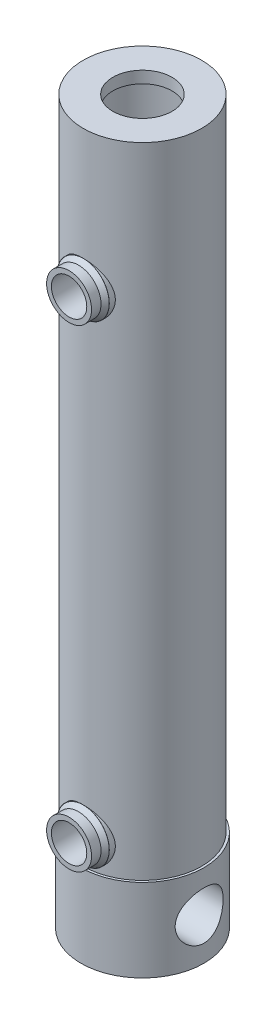
SolidWorks part; units mm, degrees
ref_plane "Plan de face" through (0, 0, 0) normal (0, 0, 1) x (1, 0, 0)
ref_plane "Plan de dessus" through (0, 0, 0) normal (0, 1, 0) x (1, 0, 0)
ref_plane "Plan de droite" through (0, 0, 0) normal (1, 0, 0) x (0, 0, -1)
sketch "Esquisse1" plane through (0, 0, 0) normal (0, 0, 1) x (1, 0, 0)
  line L0 (0, 0) -> (25, 0)
  line L1 (25, 0) -> (25, 270)
  line L2 (25, 270) -> (12.5, 270)
  line L3 (12.5, 270) -> (12.5, 265)
  line L4 (12.5, 265) -> (20, 265)
  line L5 (20, 265) -> (20, 3)
  line L6 (20, 3) -> (0, 3)
  line L7 (0, 3) -> (0, 0)
  line L8 (0, 3) -> (0, 270) construction
  line L9 (0, 270) -> (12.5, 270) construction
  dimension "D1" = 25
  dimension "D2" = 20
  dimension "D3" = 3
  dimension "D4" = 5
  dimension "D5" = 12.5
  dimension "D6" = 270
revolve "Révolution1" add sketch "Esquisse1" angle 360 about L8
sketch "Esquisse2" plane through (0, 0, 0) normal (0, -1, 0) x (-1, 0, 0)
  circle A0 centre (0, 0) radius 26
  dimension "D1" = 52
extrude "Boss.-Extru.1" add sketch "Esquisse2" along normal blind 35
sketch "Esquisse3" plane through (0, 0, 0) normal (0, 0, 1) x (1, 0, 0)
  line L0 (0, -17.5) -> (0, 0) construction
  line L1 (0, 0) -> (0, 211.5) construction
  circle A0 centre (0, -17.5) radius 10.125 construction
  circle A1 centre (0, 11.5) radius 7.475
  circle A2 centre (0, 211.5) radius 7.475
  dimension "D1" = 20.25
  dimension "D2" = 17.5
  dimension "D3" = 14.95
  dimension "D4" = 14.95
  dimension "D5" = 29
  dimension "D6" = 200
extrude "Enlèv. mat.-Extru.2" cut sketch "Esquisse3" along normal through all
sketch "Esquisse4" plane through (0, 0, 0) normal (1, 0, 0) x (0, 0, -1)
  circle A0 centre (0, -17.5) radius 10.125
  dimension "D1" = 20.25
extrude "Enlèv. mat.-Extru.3" cut sketch "Esquisse4" against normal through all both and the other way through all
ref_plane "Plan1" through (0, 0, 25) normal (0, 0, 1) x (1, 0, 0)
sketch "Esquisse5" plane through (0, 0, 25) normal (0, 0, 1) x (1, 0, 0)
  circle A0 centre (0, 211.5) radius 11
  circle A1 centre (0, 11.5) radius 11
  circle A2 centre (0, 211.5) radius 7.475
  circle A3 centre (0, 11.5) radius 7.475
  dimension "D1" = 22
  dimension "D2" = 22
extrude "Boss.-Extru.2" add sketch "Esquisse5" against normal up to next
sketch "Esquisse6" plane through (0, 0, 25) normal (0, 0, 1) x (1, 0, 0)
  circle A0 centre (0, 211.5) radius 7.475
  circle A1 centre (0, 211.5) radius 9.5
  circle A2 centre (0, 11.5) radius 7.475
  circle A3 centre (0, 11.5) radius 9.5
  dimension "D1" = 19
  dimension "D2" = 19
extrude "Boss.-Extru.3" add sketch "Esquisse6" along normal blind 6
chamfer "Chanfrein2" distance 2 angle 36 2 edges at (9.5, 211.5, 25) (9.5, 11.5, 25)
